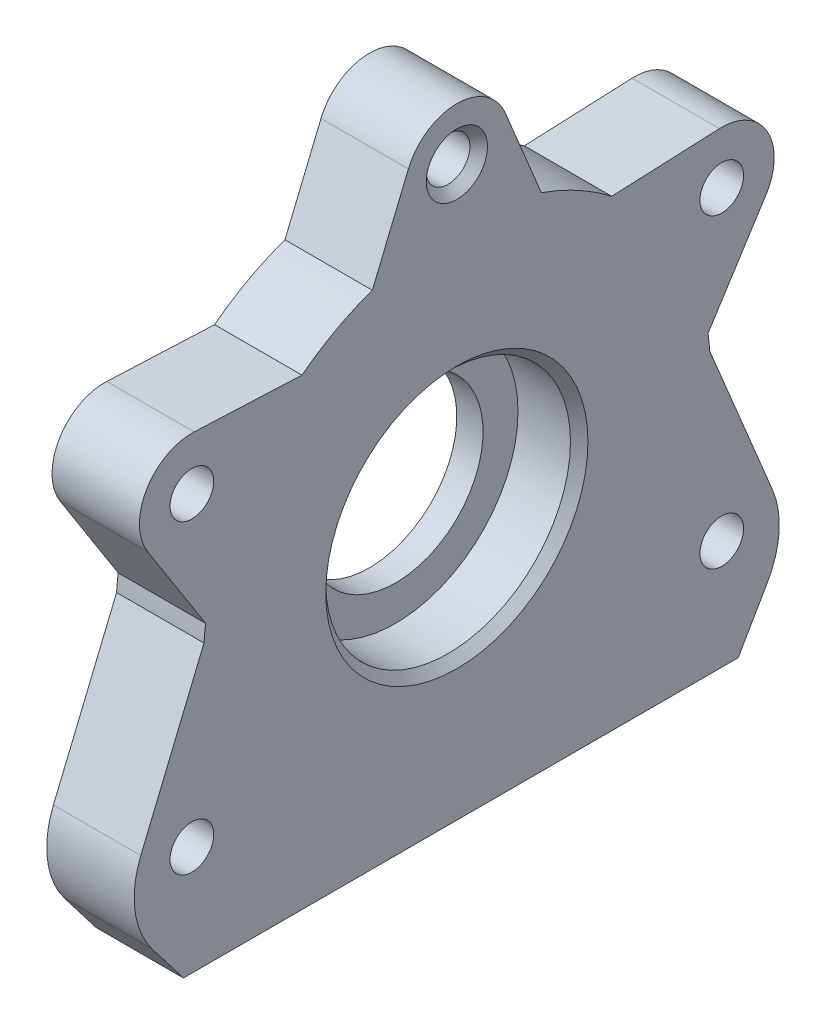
SolidWorks part; units mm, degrees
material "3.0205 (EN-AW 1200)"
ref_plane "Спереди" through (0, 0, 0) normal (0, 0, 1) x (1, 0, 0)
ref_plane "Сверху" through (0, 0, 0) normal (0, 1, 0) x (1, 0, 0)
ref_plane "Справа" through (0, 0, 0) normal (1, 0, 0) x (0, 0, -1)
sketch "Эскиз1" plane through (0, 0, 0) normal (0, 0, 1) x (1, 0, 0)
  line L0 (0, 14) -> (0, 29)
  line L1 (0, 29) -> (10, 29)
  line L2 (10, 29) -> (10, 14)
  line L3 (10, 14) -> (0, 14)
  line L4 (-29.3651, 0) -> (90.6978, 0) construction
  dimension "D1" = 28
  dimension "D2" = 15
  dimension "D3" = 10
revolve "Повернуть1" add sketch "Эскиз1" angle 360 about L4
sketch "Эскиз6" plane through (0, 0, 0) normal (-1, 0, 0) x (0, 0, 1)
  circle A0 centre (0, 0) radius 14
  circle A1 centre (0, 0) radius 10
  dimension "D1" = 28
  dimension "D2" = 20
extrude "Бобышка-Вытянуть1" add sketch "Эскиз6" against normal blind 3
sketch "Эскиз7" plane through (0, 0, 0) normal (-1, 0, 0) x (0, 0, 1)
  line L0 (-42.1922, -30) -> (42.1922, -30)
  line L1 (0, 0) -> (0, -67.0529) construction
  line L2 (-42.1922, -30) -> (-25.4067, 10.5238)
  line L3 (42.1922, -30) -> (25.4067, 10.5238)
  arc A0 (25.4067, 10.5238) -> (-25.4067, 10.5238) centre (0, 0) ccw
  circle A1 centre (0, 0) radius 28 construction
  circle A2 centre (0, 0) radius 19.5
  point P11 (42.1922, -30)
  dimension "D1" = 55
  dimension "D2" = 56
  dimension "D5" = 39
  dimension "D3" = 30
  dimension "D4" = 45
extrude "Бобышка-Вытянуть2" add sketch "Эскиз7" against normal up to surface (10 mm away) up to face at (10, 0, 29)
sketch "Эскиз10" plane through (0, 0, 0) normal (-1, 0, 0) x (0, 0, 1)
  line L0 (0, 0) -> (-30.3109, 17.5) construction
  line L1 (0, 0) -> (0, 49716.9108) construction
  line L2 (-17.8628, 0) -> (-50017.8628, 0) construction
  line L3 (-35.3712, 14.2762) -> (-28.7408, 3.8685)
  line L4 (-30.0492, 23.4943) -> (-17.7206, 22.956)
  line L5 (30.0492, 23.4943) -> (17.7206, 22.956)
  line L6 (35.3712, 14.2762) -> (28.7408, 3.8685)
  circle A0 centre (0, 0) radius 35 construction
  arc A1 (-30.0492, 23.4943) -> (-35.3712, 14.2762) centre (-30.3109, 17.5) ccw
  arc A2 (28.9297, 2.0186) -> (-28.9297, 2.0186) centre (0, 0) ccw construction
  arc A3 (-28.7408, 3.8685) -> (-17.7206, 22.956) centre (0, 0) cw
  arc A4 (28.7408, 3.8685) -> (17.7206, 22.956) centre (0, 0) ccw
  arc A5 (30.0492, 23.4943) -> (35.3712, 14.2762) centre (30.3109, 17.5) cw
  dimension "D1" = 70
  dimension "D3" = 6
  dimension "D2" = 60
  dimension "D4" = 55
extrude "Бобышка-Вытянуть3" add sketch "Эскиз10" against normal blind 10
sketch "Эскиз14" plane through (10, 0, 0) normal (1, 0, 0) x (0, 0, -1)
  line L0 (0, -6.5215) -> (0, 49993.4785) construction
  line L1 (-5.5433, 37.2961) -> (-9.6666, 27.3415)
  line L2 (5.5433, 37.2961) -> (9.6666, 27.3415)
  arc A0 (5.5433, 37.2961) -> (-5.5433, 37.2961) centre (0, 35) ccw
  arc A1 (17.7206, 22.956) -> (-17.7206, 22.956) centre (0, 0) ccw construction
  arc A2 (9.6666, 27.3415) -> (-9.6666, 27.3415) centre (0, 0) ccw
  dimension "D2" = 6
  dimension "D1" = 35
  dimension "D3" = 45
extrude "Бобышка-Вытянуть4" add sketch "Эскиз14" against normal blind 10
hole_wizard "Отверстие обработанное метчиком M43" positions "Эскиз8" profile "Эскиз9" tap size "M4" standard "DIN"
sketch "Эскиз8" plane through (0, -30, 0) normal (0, -1, 0) x (-1, 0, 0)
  line L0 (-5, 27.2261) -> (-5, -49.5848) construction
  line L2 (-30.6259, 0) -> (48.7419, 0) construction
  line L3 (0, 42.1922) -> (0, -42.1922) construction
  point P18 (-5, 25)
  point P22 (-5, -25)
  point P27 (-5, 0)
  dimension "D1" = 50
  dimension "D2" = 5
sketch "Эскиз9" plane through (5, -30, 0) normal (1, 0, 0) x (0, 0, -1)
  line L0 (0, 0) -> (0, 10.9914)
  line L1 (0, 10.9914) -> (1.65, 10)
  line L2 (1.65, 10) -> (1.65, 0.85)
  line L3 (1.65, 0.85) -> (2.5, 0)
  line L5 (2.5, 0) -> (0, 0)
  line L6 (-1.65, 0.85) -> (-2.5, 0) construction
  line L10 (0, 10.9914) -> (-1.65, 10) construction
  line L11 (0, -6.35) -> (0, 107.95) construction
  dimension "Диаметр сверла" = 3.3
  dimension "Глубина сверла" = 10
  dimension "Диаметр передней зенковки" = 5
  dimension "Угол передней зенковки" = 90
  dimension "Угол заточки сверла" = 118
cosmetic thread "Отверстие резьбы11" parameters "D1"=8, "D2"=4
cosmetic thread "Отверстие резьбы12" parameters "D1"=8, "D2"=4
cosmetic thread "Отверстие резьбы13" parameters "D1"=8, "D2"=4
sketch "Эскиз13" plane through (0, 0, 0) normal (1, 0, 0) x (0, 0, -1)
  line L0 (-32.9252, -19.0093) -> (25.8956, 14.9509) construction
  line L2 (-24.0454, 13.8826) -> (25.8956, -14.9509) construction
  line L3 (0, 0) -> (0, 50000) construction
  circle A0 centre (0, 0) radius 35 construction
  point P0 (30.3109, 17.5)
  point P4 (-30.3109, 17.5)
  point P10 (-30.3109, -17.5)
  point P23 (30.3109, -17.5)
  dimension "D2" = 70
  dimension "D1" = 60
  dimension "D3" = 60
hole_wizard "Отверстие обработанное метчиком M61" positions "Эскиз13" profile "Эскиз12" tap size "M6" standard "DIN" end condition through all
sketch "Эскиз12" plane through (0, 17.5, -30.3109) normal (0, 1, 0) x (0, 0, 1)
  line L0 (0, 0) -> (0, 10)
  line L1 (0, 10) -> (2.5, 10)
  line L2 (2.5, 10) -> (2.5, 1)
  line L3 (2.5, 1) -> (3.5, 0)
  line L5 (3.5, 0) -> (0, 0)
  line L6 (-2.5, 1) -> (-3.5, 0) construction
  line L11 (0, -6.35) -> (0, 107.95) construction
  dimension "Диаметр проходного сверла" = 5
  dimension "Глубина проходного сверла" = 10
  dimension "Диаметр передней зенковки" = 7
  dimension "Угол передней зенковки" = 90
cosmetic thread "Отверстие резьбы15" parameters "D2"=6
cosmetic thread "Отверстие резьбы16" parameters "D2"=6
cosmetic thread "Отверстие резьбы18" parameters "D2"=6
cosmetic thread "Отверстие резьбы19" parameters "D2"=6
sketch "Эскиз17" plane through (10, 0, 0) normal (1, 0, 0) x (0, 0, -1)
  point P0 (0, 35)
hole_wizard "Отверстие обработанное метчиком M62" positions "Эскиз17" profile "Эскиз16" tap size "M6" standard "DIN" end condition through all
cosmetic thread "Отверстие резьбы20" parameters "D2"=6
sketch "Эскиз16" plane through (10, 35, 0) normal (0, 1, 0) x (0, 0, -1)
  line L0 (0, 0) -> (0, 10)
  line L1 (0, 10) -> (2.5, 10)
  line L2 (2.5, 10) -> (2.5, 1)
  line L3 (2.5, 1) -> (3.5, 0)
  line L5 (3.5, 0) -> (0, 0)
  line L6 (-2.5, 1) -> (-3.5, 0) construction
  line L11 (0, -6.35) -> (0, 107.95) construction
  dimension "Диаметр проходного сверла" = 5
  dimension "Глубина проходного сверла" = 10
  dimension "Диаметр передней зенковки" = 7
  dimension "Угол передней зенковки" = 90
chamfer "Фаска1" distance 1 angle 45 1 edges at (10, 0, 14)
chamfer "Фаска2" distance 10 angle 60 2 edges at (5, -30, 42.1922) (5, -30, -42.1922)
fillet "Скругление1" radius 10 2 edges at (5, -19.9149, -38.0148) (5, -20.7612, 38.3654)
